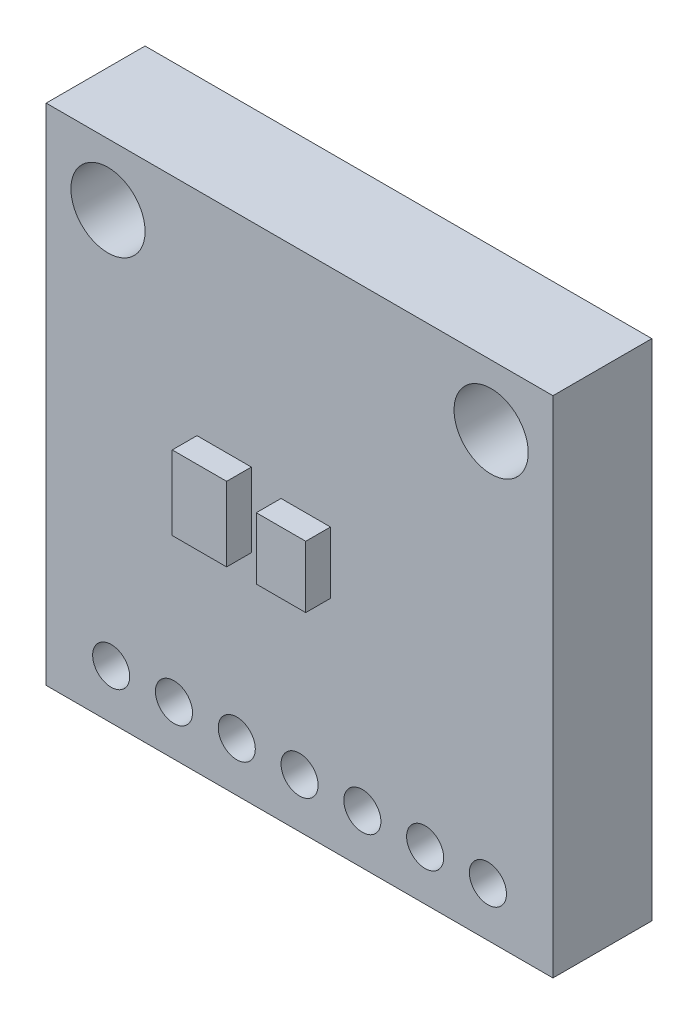
SolidWorks part; units mm, degrees
ref_plane "Plan de face" through (0, 0, 0) normal (0, 0, 1) x (1, 0, 0)
ref_plane "Plan de dessus" through (0, 0, 0) normal (0, 1, 0) x (1, 0, 0)
ref_plane "Plan de droite" through (0, 0, 0) normal (1, 0, 0) x (0, 0, -1)
sketch "Esquisse2" plane through (0, 0, 0) normal (0, 0, 1) x (1, 0, 0)
  line L0 (-5.7875, -8.7314) -> (-4.3835, -8.6587) construction
  line L2 (0, 0) -> (20.5, 0)
  line L3 (0, 0) -> (0, 20.4)
  line L4 (0, 20.4) -> (20.5, 20.4)
  line L5 (20.5, 0) -> (20.5, 20.4)
  dimension "D1" = 20.5
  dimension "D2" = 20.4
extrude "Boss.-Extru.1" add sketch "Esquisse2" against normal blind 4
sketch "Esquisse3" plane through (0, 0, 0) normal (0, 0, 1) x (1, 0, 0)
  line L0 (2.5, 17.9) -> (18, 17.9) construction
  line L1 (10.25, 20.4) -> (10.25, 0) construction
  line L2 (20.5, 20.4) -> (0, 20.4) construction
  line L3 (0, 0) -> (20.5, 0) construction
  circle A0 centre (2.5, 17.9) radius 1.5
  circle A1 centre (18, 17.9) radius 1.5
  circle A2 centre (2.63, 2) radius 0.75
  circle A3 centre (5.17, 2) radius 0.75
  circle A4 centre (7.71, 2) radius 0.75
  circle A5 centre (10.25, 2) radius 0.75
  circle A6 centre (12.79, 2) radius 0.75
  circle A7 centre (15.33, 2) radius 0.75
  circle A8 centre (17.87, 2) radius 0.75
  point P24 (10.25, 17.9)
  dimension "D2" = 2
  dimension "D3" = 2.54
  dimension "D4" = 1.5
  dimension "D5" = 15.5
  dimension "D6" = 2.5
  dimension "D7" = 3
  dimension "D1" = 7
extrude "Enlèv. mat.-Extru.1" cut sketch "Esquisse3" against normal through all
sketch "Esquisse4" plane through (0, 0, 0) normal (0, 0, 1) x (1, 0, 0)
  line L0 (0, 20.4) -> (0, 0) construction
  line L1 (6.1, 11.8) -> (8.3, 11.8)
  line L2 (6.1, 11.8) -> (6.1, 8.8)
  line L3 (6.1, 8.8) -> (8.3, 8.8)
  line L4 (8.3, 11.8) -> (8.3, 8.8)
  line L5 (9.5, 11.3) -> (11.5, 11.3)
  line L6 (9.5, 11.3) -> (9.5, 8.8)
  line L7 (9.5, 8.8) -> (11.5, 8.8)
  line L8 (11.5, 11.3) -> (11.5, 8.8)
  line L9 (0, 0) -> (20.5, 0) construction
  line L11 (40, 120) -> (200, 120) construction
  dimension "D1" = 2.5
  dimension "D2" = 2
  dimension "D3" = 2.2
  dimension "D4" = 3
  dimension "D5" = 6.1
  dimension "D6" = 8.8
  dimension "D7" = 9.5
  dimension "D8" = 8.8
extrude "Boss.-Extru.2" add sketch "Esquisse4" along normal blind 1 separate body
